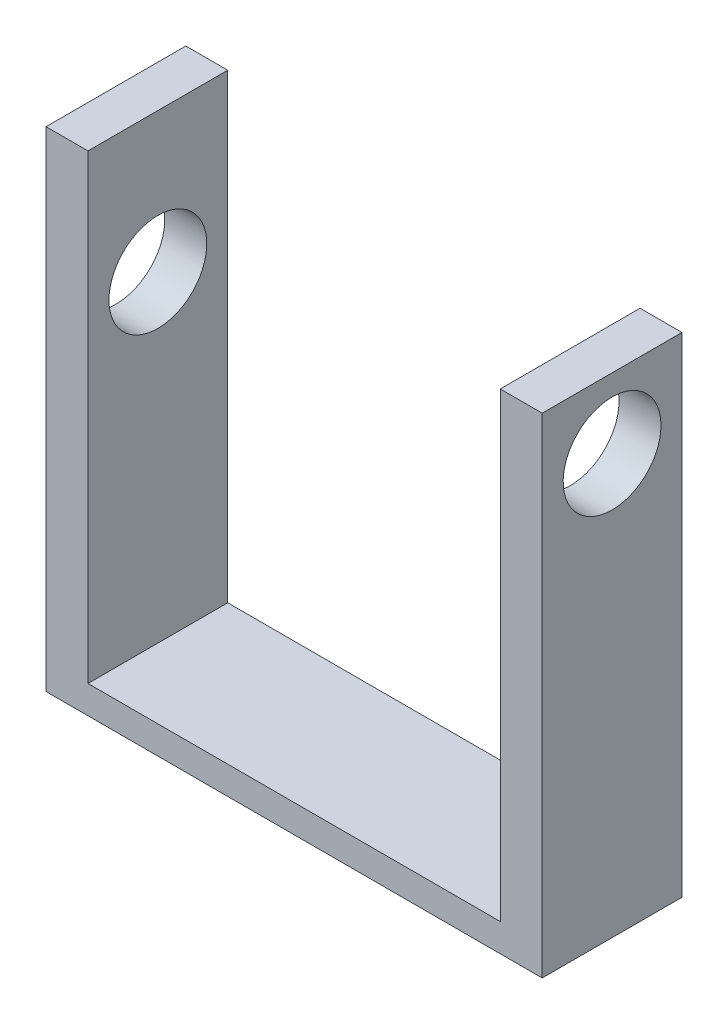
SolidWorks part; units mm, degrees
ref_plane "Front Plane" through (0, 0, 0) normal (0, 0, 1) x (1, 0, 0)
ref_plane "Top Plane" through (0, 0, 0) normal (0, 1, 0) x (1, 0, 0)
ref_plane "Right Plane" through (0, 0, 0) normal (1, 0, 0) x (0, 0, -1)
sketch "Sketch1" plane through (0, 0, 0) normal (0, 0, 1) x (1, 0, 0)
  line L0 (14.75, 2) -> (-14.75, 2)
  line L1 (-14.75, 2) -> (-14.75, 35)
  line L2 (-14.75, 35) -> (-17.75, 35)
  line L3 (-17.75, 35) -> (-17.75, 0)
  line L4 (-17.75, 0) -> (17.75, 0)
  line L5 (17.75, 0) -> (17.75, 35)
  line L6 (17.75, 35) -> (14.75, 35)
  line L7 (14.75, 35) -> (14.75, 2)
  point P3 (0, 0)
  point P4 (0, 0)
  point P9 (0, 0)
  point P12 (9.2803, -1.107)
  point P13 (11.3064, 30)
  dimension "D1" = 29.5
  dimension "D2" = 35
  dimension "D3" = 2
  dimension "D4" = 3
extrude "Boss-Extrude1" add sketch "Sketch1" along normal mid plane 10
sketch "Sketch2" plane through (17.75, 0, 0) normal (1, 0, 0) x (0, 0, -1)
  circle A0 centre (0, 30) radius 3.5
  point P2 (0, 0)
  dimension "D1" = 7
  dimension "D2" = 30
extrude "Cut-Extrude1" cut sketch "Sketch2" against normal mid plane 10
sketch "Sketch3" plane through (-17.75, 0, 0) normal (-1, 0, 0) x (0, 0, 1)
  line L0 (5, 0) -> (-5, 0) construction
  circle A0 centre (0, 25) radius 3.5
  dimension "D1" = 7
  dimension "D2" = 25
extrude "Cut-Extrude2" cut sketch "Sketch3" against normal up to next
